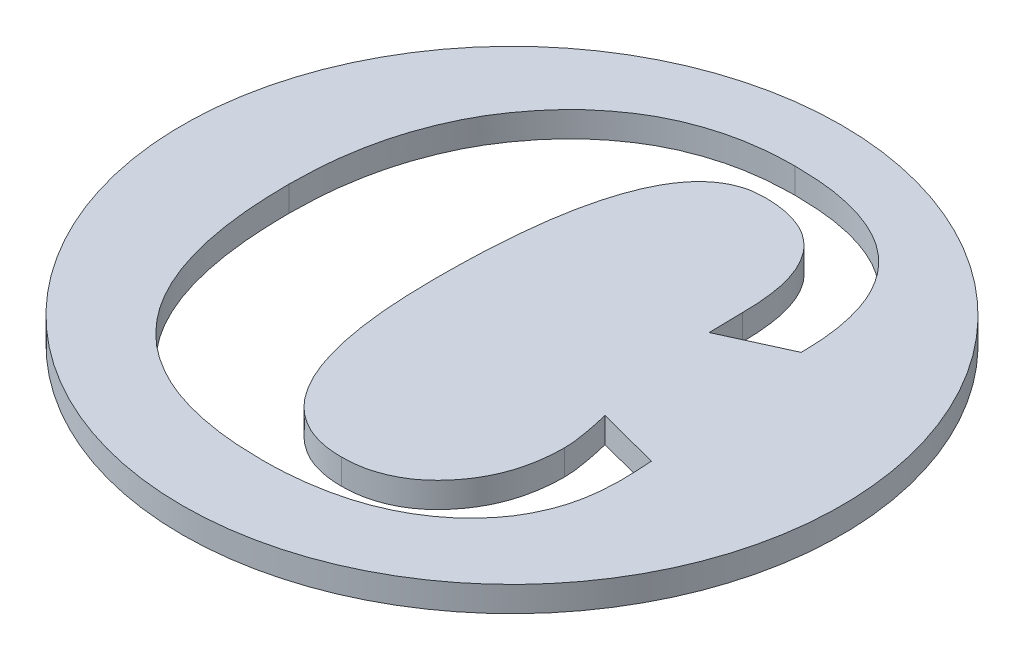
SolidWorks part; units mm, degrees
ref_plane "Front Plane" through (0, 0, 0) normal (0, 0, 1) x (1, 0, 0)
ref_plane "Top Plane" through (0, 0, 0) normal (0, 1, 0) x (1, 0, 0)
ref_plane "Right Plane" through (0, 0, 0) normal (1, 0, 0) x (0, 0, -1)
sketch "Sketch1" plane through (0, 0, 0) normal (0, 1, 0) x (1, 0, 0)
  circle A0 centre (0, 0) radius 13
  dimension "D1" = 26
extrude "Boss-Extrude1" add sketch "Sketch1" along normal blind 1
sketch "Sketch2" plane through (0, 1, 0) normal (0, 1, 0) x (1, 0, 0)
  text T0 "C" font "Britannic Bold" height 20
extrude "Cut-Extrude1" cut sketch "Sketch2" against normal blind 1
